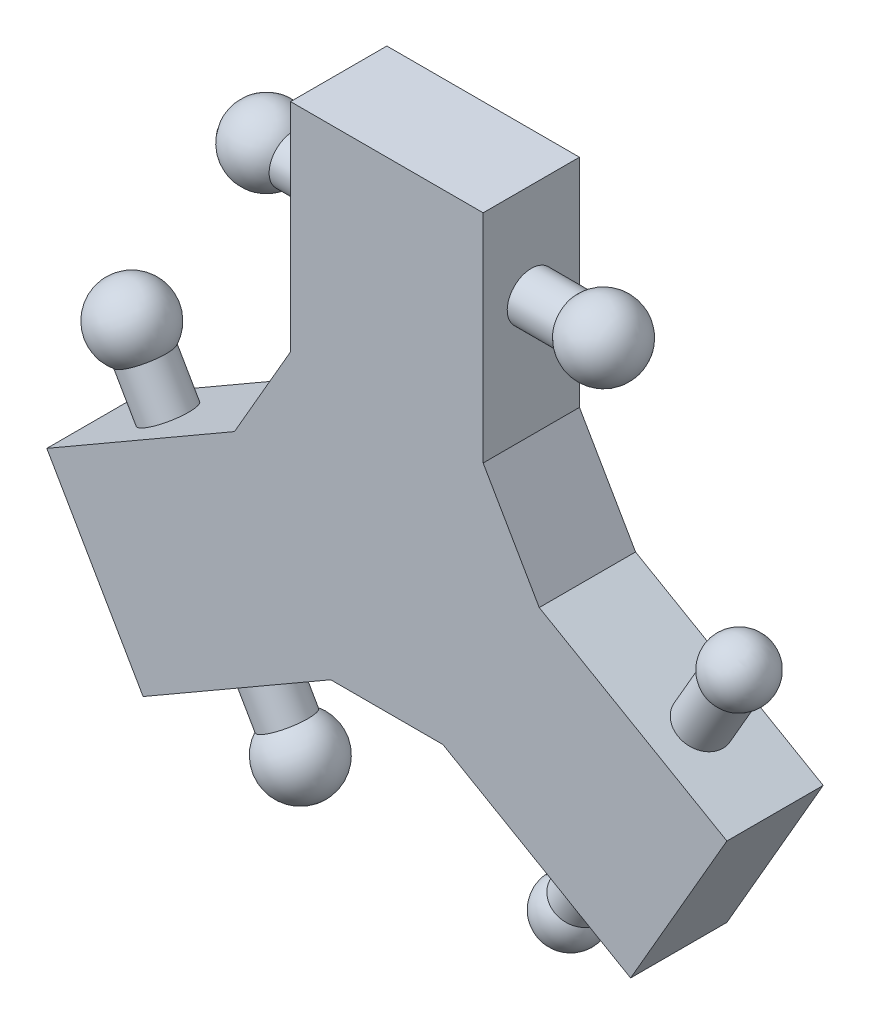
SolidWorks part; units mm, degrees
ref_plane "Front Plane" through (0, 0, 0) normal (0, 0, 1) x (1, 0, 0)
ref_plane "Top Plane" through (0, 0, 0) normal (0, 1, 0) x (1, 0, 0)
ref_plane "Right Plane" through (0, 0, 0) normal (1, 0, 0) x (0, 0, -1)
sketch "Sketch1" plane through (0, 0, 0) normal (0, 0, 1) x (1, 0, 0)
  line L0 (0, -1000) -> (0, 49000) construction
  line L1 (-1000, 0) -> (49000, 0) construction
  line L2 (-4, 20) -> (4, 20)
  line L3 (4, 20) -> (4, 11)
  line L4 (-4, 20) -> (-4, 11)
  line L5 (14.1244, 2.4641) -> (10.1244, -4.4641)
  line L6 (14.1244, 2.4641) -> (6.3301, 6.9641)
  line L7 (10.1244, -4.4641) -> (2.3301, 0.0359)
  line L8 (-10.1244, -4.4641) -> (-14.1244, 2.4641)
  line L9 (-10.1244, -4.4641) -> (-2.3301, 0.0359)
  line L10 (-14.1244, 2.4641) -> (-6.3301, 6.9641)
  line L11 (-6.3301, 6.9641) -> (-4, 11)
  line L12 (4, 11) -> (6.3301, 6.9641)
  line L13 (2.3301, 0.0359) -> (-2.3301, 0.0359)
  dimension "D1" = 9
  dimension "D2" = 9
  dimension "D3" = 4
  dimension "D4" = 4
  dimension "D5" = 20
  dimension "D6" = 3
extrude "Boss-Extrude1" add sketch "Sketch1" along normal blind 4
sketch "Sketch4" plane through (-0.5981, 1.0359, 0) normal (0.5, -0.866, 0) x (0.866, 0.5, 0)
  line L0 (-7.5, -997.5603) -> (-7.5, 49002.4397) construction
  line L1 (-10, -997.7252) -> (-10, 49002.2748) construction
  line L3 (-5, -996.5243) -> (-5, 49003.4757) construction
  line L5 (-1008.0271, 0) -> (48991.9729, 0) construction
  line L7 (-1008.056, 4) -> (48991.944, 4) construction
  line L9 (-1008.3164, 2) -> (48991.6836, 2) construction
  circle A0 centre (-7.5, 2) radius 1
  dimension "D5" = 2
  dimension "D1" = 4
  dimension "D2" = 2
  dimension "D3" = 5
  dimension "D4" = 2.5
extrude "Boss-Extrude2" add sketch "Sketch4" along normal blind 3
sketch3d "3DSketch2"
  line L0 (0, 0, 0) -> (0, 0, 50000) construction
pattern_circular "CirPattern1" count 3 over 360 about axis through (0, 0, 0) along (0, 0, 1) of "Boss-Extrude2"
sketch "Sketch6" plane through (3.5, 6.0622, 0) normal (0.5, 0.866, 0) x (0.866, -0.5, 0)
  line L0 (7.4869, -1001.9517) -> (7.4869, 48998.0483) construction
  line L1 (-992.5131, -1.9517) -> (49007.4869, -1.9517) construction
  line L2 (7.4869, -0.6792) -> (7.4869, -3.2242)
  line L3 (7.4869, -3.2242) -> (7.4765, -3.2138)
  arc A0 (7.4869, -3.2242) -> (7.4869, -0.6792) centre (7.4869, -1.9517) ccw
revolve "Revolve1" add sketch "Sketch6" angle 360 about L0
sketch "Sketch8" plane through (0.5981, 1.0359, 0) normal (-0.5, -0.866, 0) x (0.866, -0.5, 0)
  circle A0 centre (7.5, 2) radius 1
extrude "Boss-Extrude3" add sketch "Sketch8" along normal blind 3
sketch "Sketch9" plane through (-0.9019, -1.5622, 0) normal (-0.5, -0.866, 0) x (0.866, -0.5, 0)
  line L0 (7.4869, -998.0483) -> (7.4869, 49001.9517) construction
  line L1 (7.4869, 3.2242) -> (7.4869, 0.6792)
  arc A0 (7.4869, 0.6792) -> (7.4869, 3.2242) centre (7.4869, 1.9517) ccw
revolve "Revolve2" add sketch "Sketch9" angle 360 about L0
sketch "Sketch10" plane through (0.9019, -1.5622, 0) normal (0.5, -0.866, 0) x (0.866, 0.5, 0)
  line L0 (-7.5, -998) -> (-7.5, 49002) construction
  line L1 (-1006.5, 2) -> (48993.5, 2) construction
  line L2 (-7.5, 3.5) -> (-7.5, 0.5)
  arc A1 (-7.5, 0.5) -> (-7.5, 3.5) centre (-7.5, 2) ccw
  dimension "D1" = 3
revolve "Revolve3" add sketch "Sketch10" angle 360 about L0
sketch "Sketch11" plane through (-4.5981, 7.9641, 0) normal (-0.5, 0.866, 0) x (0.866, 0.5, 0)
  circle A0 centre (-7.5, -2) radius 1
extrude "Boss-Extrude4" add sketch "Sketch11" along normal blind 3
sketch "Sketch12" plane through (-6.0981, 10.5622, 0) normal (-0.5, 0.866, 0) x (0.866, 0.5, 0)
  line L0 (-7.5, -1002) -> (-7.5, 48998) construction
  line L1 (-7.5, -0.5) -> (-7.5, -3.5)
  line L2 (-7.5, -3.5) -> (-7.5192, -3.4664)
  arc A0 (-7.5, -3.5) -> (-7.5, -0.5) centre (-7.5, -2) ccw
revolve "Revolve4" add sketch "Sketch12" angle 360 about L0
sketch "Sketch16" plane through (4.5981, 7.9641, 0) normal (0.5, 0.866, 0) x (0.866, -0.5, 0)
  circle A0 centre (7.5, -2) radius 1
extrude "Boss-Extrude6" add sketch "Sketch16" along normal blind 3
sketch "Sketch17" plane through (6.0981, 10.5622, 0) normal (0.5, 0.866, 0) x (0.866, -0.5, 0)
  line L0 (7.4869, -1001.9517) -> (7.4869, 48998.0483) construction
  line L1 (7.4869, -0.6792) -> (7.4869, -3.2242)
  line L2 (7.4869, -3.2242) -> (7.4869, -3.0723)
  arc A0 (7.4869, -3.2242) -> (7.4869, -0.6792) centre (7.4869, -1.9517) ccw
revolve "Revolve7" add sketch "Sketch17" angle 360 about L0
sketch "Sketch21" plane through (-4, 0, 0) normal (-1, 0, 0) x (0, 0, 1)
  line L0 (2, -200983.1349) -> (2, 249016.8651) construction
  line L1 (-200997.5146, 16) -> (249002.4854, 16) construction
  circle A0 centre (2, 16) radius 1
  dimension "D1" = 2
sketch "Sketch23" plane through (4, 0, 0) normal (1, 0, 0) x (0, 0, -1)
  circle A0 centre (-2, 16) radius 1
extrude "Boss-Extrude8" add sketch "Sketch23" along normal blind 3
sketch "Sketch25" plane through (7, 0, 0) normal (1, 0, 0) x (0, 0, -1)
  line L0 (-2, -984) -> (-2, 49016) construction
  line L1 (-2, 17.5) -> (-2, 14.5)
  arc A0 (-2, 14.5) -> (-2, 17.5) centre (-2, 16) ccw
revolve "Revolve9" add sketch "Sketch25" angle 360 about L0
extrude "Boss-Extrude9" add sketch "Sketch21" along normal blind 3
sketch "Sketch26" plane through (-7, 0, 0) normal (-1, 0, 0) x (0, 0, 1)
  line L0 (2, -984) -> (2, 49016) construction
  line L1 (2, 17.5067) -> (2, 14.5183)
  arc A0 (2, 14.5183) -> (2, 17.5067) centre (2, 16.0125) ccw
revolve "Revolve10" add sketch "Sketch26" angle 360 about L0
